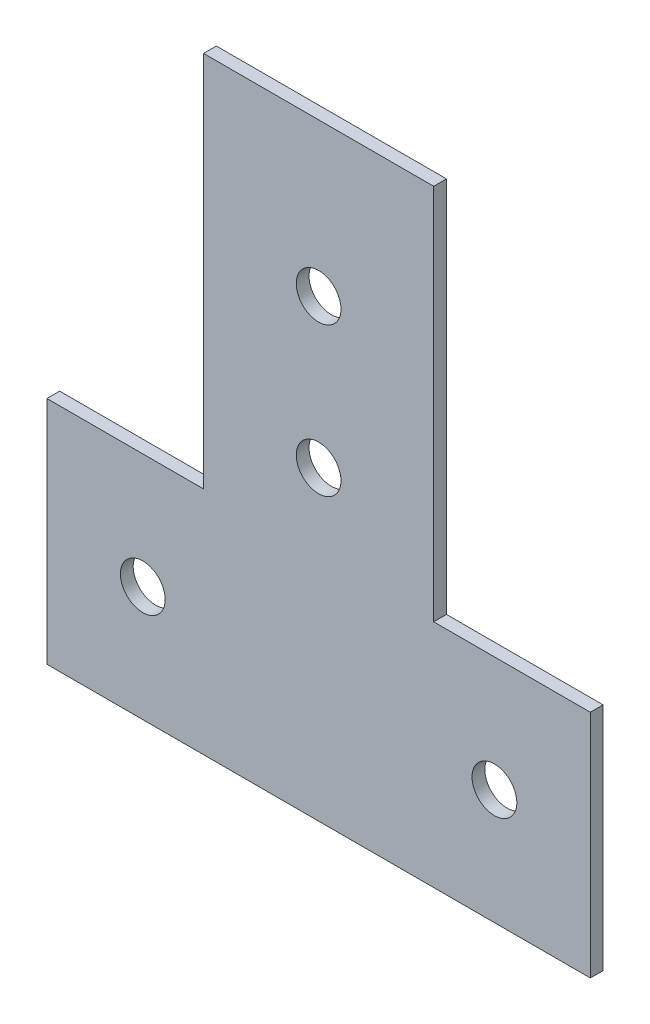
SolidWorks part; units mm, degrees
ref_plane "前视基准面" through (0, 0, 0) normal (0, 0, 1) x (1, 0, 0)
ref_plane "上视基准面" through (0, 0, 0) normal (0, 1, 0) x (1, 0, 0)
ref_plane "右视基准面" through (0, 0, 0) normal (1, 0, 0) x (0, 0, -1)
sketch "草图1" plane through (0, 0, 0) normal (0, 0, 1) x (1, 0, 0)
  line L1 (-42.5, -18) -> (42.5, -18)
  line L2 (-42.5, -18) -> (-42.5, 18)
  line L3 (-42.5, 18) -> (-18, 18)
  line L4 (42.5, -18) -> (42.5, 18)
  line L5 (-42.5, -18) -> (42.5, 18) construction
  line L6 (-42.5, 18) -> (42.5, -18) construction
  line L9 (-18, 77) -> (18, 77)
  line L10 (18, 18) -> (42.5, 18)
  line L11 (-18, 18) -> (-18, 77)
  line L12 (18, 18) -> (18, 77)
  point P0 (0, 0)
  point P6 (0, 77)
  dimension "D1" = 36
  dimension "D2" = 85
  dimension "D3" = 36
extrude "凸台-拉伸1" add sketch "草图1" along normal blind 2
sketch "草图2" plane through (0, 0, 2) normal (0, 0, 1) x (1, 0, 0)
  line L0 (0, 0) -> (0, 16.8919) construction
  line L1 (42.5, -18) -> (42.5, 18) construction
  circle A0 centre (0, 53.0963) radius 3.5
  circle A1 centre (0, 29.8522) radius 3.5
  circle A2 centre (-27.5, 0) radius 3.5
  circle A3 centre (27.5, 0) radius 3.5
  dimension "D1" = 7
  dimension "D2" = 7
  dimension "D3" = 7
  dimension "D4" = 15
extrude "切除-拉伸1" cut sketch "草图2" against normal through all
